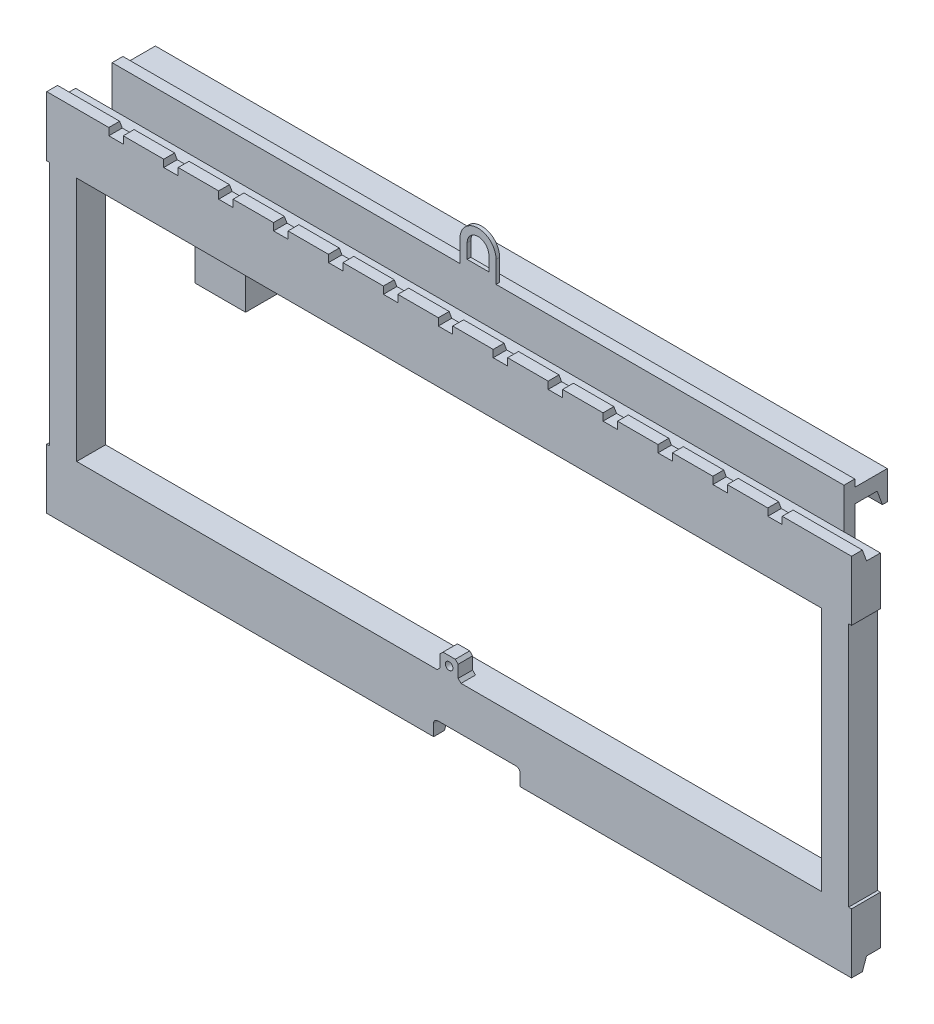
SolidWorks part; units mm, degrees
material "S235JRG2"
ref_plane "Front Plane" through (0, 0, 0) normal (0, 0, 1) x (1, 0, 0)
ref_plane "Top Plane" through (0, 0, 0) normal (0, 1, 0) x (1, 0, 0)
ref_plane "Right Plane" through (0, 0, 0) normal (1, 0, 0) x (0, 0, -1)
sketch "Sketch1" plane through (0, 0, 0) normal (1, 0, 0) x (0, 0, -1)
  line L0 (0, 0) -> (0, 83)
  line L1 (0, 83) -> (40, 83)
  line L2 (40, 83) -> (40, 16)
  line L3 (40, 16) -> (20.8235, 16)
  line L4 (20.8235, 16) -> (15, 0)
  line L5 (15, 0) -> (0, 0)
  dimension "D1" = 40
  dimension "D2" = 83
  dimension "D3" = 16
  dimension "D4" = 20
  dimension "D5" = 15
extrude "Boss-Extrude1" add sketch "Sketch1" along normal mid plane 1115
sketch "Sketch2" plane through (0, 83, 0) normal (0, 1, 0) x (1, 0, 0)
  line L0 (557.5, 40) -> (-557.5, 40) construction
  line L1 (-553.5, 40) -> (-516, 40)
  line L2 (-553.5, 40) -> (-553.5, 0)
  line L3 (-553.5, 0) -> (-516, 0)
  line L4 (-516, 40) -> (-516, 0)
  line L5 (557.5, 0) -> (-557.5, 0) construction
  line L6 (-557.5, 40) -> (-557.5, 0) construction
  line L7 (0, 0) -> (0, 78.0192) construction
  line L8 (516, 40) -> (516, 0)
  line L9 (553.5, 0) -> (516, 0)
  line L10 (553.5, 40) -> (553.5, 0)
  line L11 (553.5, 40) -> (516, 40)
  dimension "D1" = 37.5
  dimension "D2" = 4
extrude "Boss-Extrude2" add sketch "Sketch2" along normal blind 340
sketch "Sketch3" plane through (557.5, 0, 0) normal (1, 0, 0) x (0, 0, -1)
  line L0 (0, 423) -> (0, 506)
  line L1 (0, 506) -> (15, 506)
  line L2 (15, 506) -> (20.8235, 490)
  line L3 (20.8235, 490) -> (40, 490)
  line L4 (40, 490) -> (40, 423)
  line L5 (40, 423) -> (0, 423)
  dimension "D1" = 83
  dimension "D2" = 15
  dimension "D3" = 20
  dimension "D4" = 16
extrude "Boss-Extrude3" add sketch "Sketch3" against normal up to surface (1115 mm away) up to face at (-557.5, 33, -19.3039)
sketch "Sketch4" plane through (0, 0, 0) normal (0, 0, 1) x (1, 0, 0)
  line L0 (557.5, 0) -> (-557.5, 0) construction
  line L1 (-21.5, 0) -> (98.5, 0)
  line L2 (-21.5, 0) -> (-21.5, 22)
  line L3 (-21.5, 22) -> (98.5, 22)
  line L4 (98.5, 0) -> (98.5, 22)
  line L6 (-557.5, 83) -> (-557.5, 0) construction
  dimension "D1" = 120
  dimension "D2" = 22
  dimension "D3" = 536
extrude "Cut-Extrude1" cut sketch "Sketch4" against normal through all
fillet "Fillet1" radius 6 2 edges at (98.5, 22, -20) (-21.5, 22, -20)
sketch "Sketch5" plane through (0, 0, -40) normal (0, 0, -1) x (-1, 0, 0)
  line L0 (182.5, 89) -> (424.5, 89)
  line L1 (424.5, 89) -> (424.5, -9)
  line L2 (424.5, -9) -> (408.5, -9)
  line L3 (408.5, -9) -> (372.25, -46)
  line L4 (372.25, -46) -> (234.75, -46)
  line L5 (234.75, -46) -> (198.5, -9)
  line L6 (198.5, -9) -> (182.5, -9)
  line L7 (182.5, -9) -> (182.5, 89)
  line L8 (198.5, -9) -> (408.5, -9) construction
  line L9 (303.5, -46) -> (303.5, -9) construction
  line L10 (0, 0) -> (0, 150.938) construction
  line L11 (-516, 83) -> (516, 83) construction
  line L12 (303.5, -9) -> (303.5, 89) construction
  line L13 (-303.5, -9) -> (-303.5, 89) construction
  line L14 (-303.5, -46) -> (-303.5, -9) construction
  line L15 (-198.5, -9) -> (-408.5, -9) construction
  line L16 (-182.5, -9) -> (-182.5, 89)
  line L17 (-198.5, -9) -> (-182.5, -9)
  line L18 (-234.75, -46) -> (-198.5, -9)
  line L19 (-372.25, -46) -> (-234.75, -46)
  line L20 (-408.5, -9) -> (-372.25, -46)
  line L21 (-424.5, -9) -> (-408.5, -9)
  line L22 (-424.5, 89) -> (-424.5, -9)
  line L23 (-182.5, 89) -> (-424.5, 89)
  dimension "D1" = 365
  dimension "D2" = 242
  dimension "D3" = 98
  dimension "D4" = 6
  dimension "D5" = 135
  dimension "D6" = 137.5
  dimension "D7" = 210
extrude "Boss-Extrude4" [suppressed] add sketch "Sketch5" along normal blind 15
fillet "Fillet2" [suppressed] radius 10
sketch "Sketch6" [suppressed] plane through (0, 0, -55) normal (0, 0, -1) x (-1, 0, 0)
  line L0 (238.9522, -46) -> (368.0478, -46) construction
  line L1 (239.5, -8) -> (367.5, -8)
  line L2 (239.5, -8) -> (239.5, -46)
  line L3 (239.5, -46) -> (367.5, -46)
  line L4 (367.5, -8) -> (367.5, -46)
  line L5 (239.5, -8) -> (367.5, -46) construction
  line L6 (239.5, -46) -> (367.5, -8) construction
  point P0 (303.5, -27)
  point P7 (303.5, -46)
  dimension "D1" = 128
  dimension "D2" = 38
extrude "Boss-Extrude5" [suppressed] add sketch "Sketch6" along normal blind 25
sketch "Sketch7" [suppressed] plane through (0, 0, -80) normal (0, 0, -1) x (-1, 0, 0)
  line L0 (303.5, -46) -> (303.5, -8) construction
  line L1 (239.5, -46) -> (367.5, -46) construction
  line L2 (367.5, -8) -> (239.5, -8) construction
  line L3 (303.5, -27) -> (258.5, -27) construction
  circle A0 centre (258.5, -27) radius 10
  circle A1 centre (348.5, -27) radius 10
  dimension "D1" = 20
  dimension "D2" = 45
extrude "Cut-Extrude2" [suppressed] cut sketch "Sketch7" against normal through all
mirror "Mirror1" [suppressed] about plane through (0, 0, 0) normal (1, 0, 0)
sketch "Sketch8" plane through (0, 0, 0) normal (0, 0, 1) x (1, 0, 0)
  line L0 (-557.5, 506) -> (557.5, 506) construction
  line L1 (-471.5, 506) -> (-451.5, 506)
  line L2 (-471.5, 506) -> (-471.5, 496)
  line L3 (-471.5, 496) -> (-451.5, 496)
  line L4 (-451.5, 506) -> (-451.5, 496)
  line L5 (-557.5, 506) -> (-557.5, 423) construction
  line L6 (-395.4167, 506) -> (-375.4167, 506)
  line L7 (-395.4167, 506) -> (-395.4167, 496)
  line L8 (-395.4167, 496) -> (-375.4167, 496)
  line L9 (-375.4167, 506) -> (-375.4167, 496)
  line L10 (-319.3333, 506) -> (-299.3333, 506)
  line L11 (-319.3333, 506) -> (-319.3333, 496)
  line L12 (-319.3333, 496) -> (-299.3333, 496)
  line L13 (-299.3333, 506) -> (-299.3333, 496)
  line L14 (-243.25, 506) -> (-223.25, 506)
  line L15 (-243.25, 506) -> (-243.25, 496)
  line L16 (-243.25, 496) -> (-223.25, 496)
  line L17 (-223.25, 506) -> (-223.25, 496)
  line L18 (-167.1667, 506) -> (-147.1667, 506)
  line L19 (-167.1667, 506) -> (-167.1667, 496)
  line L20 (-167.1667, 496) -> (-147.1667, 496)
  line L21 (-147.1667, 506) -> (-147.1667, 496)
  line L22 (-91.0833, 506) -> (-71.0833, 506)
  line L23 (-91.0833, 506) -> (-91.0833, 496)
  line L24 (-91.0833, 496) -> (-71.0833, 496)
  line L25 (-71.0833, 506) -> (-71.0833, 496)
  line L26 (-15, 506) -> (5, 506)
  line L27 (-15, 506) -> (-15, 496)
  line L28 (-15, 496) -> (5, 496)
  line L29 (5, 506) -> (5, 496)
  line L30 (61.0833, 506) -> (81.0833, 506)
  line L31 (61.0833, 506) -> (61.0833, 496)
  line L32 (61.0833, 496) -> (81.0833, 496)
  line L33 (81.0833, 506) -> (81.0833, 496)
  line L34 (137.1667, 506) -> (157.1667, 506)
  line L35 (137.1667, 506) -> (137.1667, 496)
  line L36 (137.1667, 496) -> (157.1667, 496)
  line L37 (157.1667, 506) -> (157.1667, 496)
  line L38 (213.25, 506) -> (233.25, 506)
  line L39 (213.25, 506) -> (213.25, 496)
  line L40 (213.25, 496) -> (233.25, 496)
  line L41 (233.25, 506) -> (233.25, 496)
  line L42 (289.3333, 506) -> (309.3333, 506)
  line L43 (289.3333, 506) -> (289.3333, 496)
  line L44 (289.3333, 496) -> (309.3333, 496)
  line L45 (309.3333, 506) -> (309.3333, 496)
  line L46 (365.4167, 506) -> (385.4167, 506)
  line L47 (365.4167, 506) -> (365.4167, 496)
  line L48 (365.4167, 496) -> (385.4167, 496)
  line L49 (385.4167, 506) -> (385.4167, 496)
  line L50 (441.5, 506) -> (461.5, 506)
  line L51 (441.5, 506) -> (441.5, 496)
  line L52 (441.5, 496) -> (461.5, 496)
  line L53 (461.5, 506) -> (461.5, 496)
  line L54 (557.5, 506) -> (557.5, 423) construction
  dimension "D1" = 20
  dimension "D2" = 10
  dimension "D3" = 86
  dimension "D5" = 96
  dimension "D4" = 13
extrude "Cut-Extrude3" cut sketch "Sketch8" against normal through all
sketch "Sketch9" plane through (0, 0, 0) normal (0, 0, 1) x (1, 0, 0)
  line L0 (516, 83) -> (-516, 83) construction
  line L1 (-12.5, 83) -> (12.5, 83)
  line L2 (-12.5, 83) -> (-12.5, 108)
  line L3 (-12.5, 108) -> (12.5, 108)
  line L4 (12.5, 83) -> (12.5, 108)
  line L5 (-12.5, 83) -> (12.5, 108) construction
  line L7 (0, 0) -> (0, 95.5) construction
  circle A0 centre (0, 95.5) radius 5.25
  dimension "D3" = 10.5
  dimension "D1" = 25
  dimension "D2" = 25
extrude "Boss-Extrude6" add sketch "Sketch9" against normal blind 20
chamfer "Chamfer1" distance 4 angle 45 4 edges at (-12.5, 108, -10) (12.5, 83, -10) (-12.5, 83, -10) (12.5, 108, -10)
sketch "Sketch10" plane through (0, 0, -40) normal (0, 0, -1) x (-1, 0, 0)
  line L0 (557.5, 490) -> (-557.5, 490) construction
  line L1 (-507, 436) -> (507, 436)
  line L2 (-507, 436) -> (-507, 546)
  line L3 (-507, 546) -> (507, 546)
  line L4 (507, 436) -> (507, 546)
  line L6 (0, 0) -> (0, 436) construction
  dimension "D1" = 1014
  dimension "D2" = 110
  dimension "D3" = 56
extrude "Boss-Extrude7" add sketch "Sketch10" along normal blind 15
sketch "Sketch11" plane through (0, 0, 0) normal (1, 0, 0) x (0, 0, -1)
  line L0 (55, 536) -> (100, 536)
  line L1 (55, 546) -> (55, 436) construction
  line L2 (100, 536) -> (100, 496)
  line L3 (100, 496) -> (93.2794, 496)
  line L4 (93.2794, 496) -> (86, 516)
  line L5 (86, 516) -> (55, 516)
  line L6 (55, 516) -> (55, 536)
  line L7 (55, 546) -> (40, 546) construction
  dimension "D1" = 45
  dimension "D2" = 10
  dimension "D3" = 20
  dimension "D4" = 20
  dimension "D5" = 40
  dimension "D6" = 14
extrude "Boss-Extrude8" add sketch "Sketch11" along normal mid plane 1014
sketch "Sketch12" plane through (0, 0, -40) normal (0, 0, 1) x (1, 0, 0)
  line L0 (-25, 546) -> (-25, 576)
  line L1 (-507, 546) -> (507, 546) construction
  line L2 (-25, 576) -> (25, 576) construction
  line L3 (25, 576) -> (25, 546)
  line L4 (25, 546) -> (-25, 546)
  line L5 (-15, 556) -> (-15, 576)
  line L6 (15, 576) -> (15, 556)
  line L7 (15, 556) -> (-15, 556)
  arc A0 (-25, 576) -> (25, 576) centre (0, 576) cw
  arc A1 (-15, 576) -> (15, 576) centre (0, 576) cw
  point P12 (0, 546)
  dimension "D1" = 50
  dimension "D2" = 30
  dimension "D3" = 10
extrude "Boss-Extrude9" add sketch "Sketch12" against normal blind 5
sketch "Sketch13" plane through (0, 0, 0) normal (0, 0, 1) x (1, 0, 0)
  line L0 (-516, 423) -> (516, 423) construction
  line L1 (-366, 423) -> (-296, 423)
  line L2 (-366, 423) -> (-366, 365)
  line L3 (-366, 365) -> (-296, 365)
  line L4 (-296, 423) -> (-296, 365)
  line L5 (-516, 423) -> (-516, 83) construction
  dimension "D1" = 70
  dimension "D2" = 58
  dimension "D3" = 150
extrude "Boss-Extrude10" add sketch "Sketch13" against normal blind 45 from offset 14
